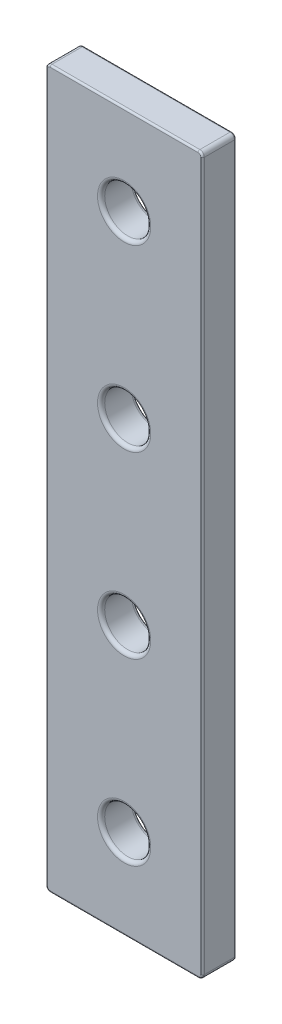
SolidWorks part; units mm, degrees
ref_plane "Front Plane" through (0, 0, 0) normal (0, 0, 1) x (1, 0, 0)
ref_plane "Top Plane" through (0, 0, 0) normal (0, 1, 0) x (1, 0, 0)
ref_plane "Right Plane" through (0, 0, 0) normal (1, 0, 0) x (0, 0, -1)
sketch "Sketch1" plane through (0, 0, 0) normal (0, 0, 1) x (1, 0, 0)
  line L0 (-11.1125, 50.8) -> (-11.1125, -50.8)
  line L1 (-11.1125, 50.8) -> (11.1125, 50.8)
  line L2 (-11.1125, -50.8) -> (11.1125, -50.8)
  line L3 (11.1125, 50.8) -> (11.1125, -50.8)
  line L4 (-11.1125, 0) -> (11.1125, 0) construction
  line L5 (0, 12.7) -> (0, 38.1) construction
  line L6 (-3.175, 38.1) -> (-1.905, 38.1) construction
  circle A0 centre (0, 38.1) radius 3.2639
  circle A2 centre (0, 38.1) radius 3.175 construction
  circle A3 centre (25.4, 38.1) radius 3.2639
  circle A4 centre (25.4, 12.7) radius 3.2639
  circle A5 centre (0, 12.7) radius 3.2639
  circle A6 centre (0, -12.7) radius 3.2639
  circle A7 centre (25.4, -12.7) radius 3.2639
  circle A8 centre (0, -38.1) radius 3.2639
  circle A9 centre (25.4, -38.1) radius 3.2639
  dimension "Thru Hole Diameter" = 6.5278
  dimension "Mounting Fastener Thread Size" = 6.35
  dimension "Width" = 22.225
  dimension "Length" = 101.6
  dimension "Mounting Hole Vert CtoC" = 25.4
  dimension "Mounting Fastener Thread Pitch" = 1.27
  dimension "D1" = 63.5
  dimension "D2" = 11.1125
  dimension "Mounting Hole Horiz CtoC" = 25.4
  dimension "Mounting Hole Vertical Offset" = 12.7
  dimension "Mounting Hole Horizontal Offset" = 11.1125
  dimension "D50" = 2
  dimension "Number of Vertical Holes" = 4
sketch "Sketch2" plane through (0, 0, 0) normal (1, 0, 0) x (0, 0, -1)
  line L0 (-2.3876, 38.1) -> (2.3876, 38.1) construction
  line L1 (2.3876, 38.1) -> (15.0749, 38.1) construction
  dimension "Thickness" = 4.7752
  dimension "Mounting Fastener Thread Length" = 17.4625
sketch "Sketch3" plane through (0, 0, 0) normal (0, 0, 1) x (1, 0, 0)
  line L0 (-11.1125, 50.8) -> (-11.1125, -50.8) construction
  line L1 (-11.1125, -50.8) -> (11.1125, -50.8) construction
  line L2 (11.1125, 50.8) -> (11.1125, -50.8) construction
  line L3 (-11.1125, 50.8) -> (11.1125, 50.8) construction
  line L4 (-11.1125, 50.8) -> (-11.1125, -50.8)
  line L5 (-11.1125, -50.8) -> (11.1125, -50.8)
  line L6 (11.1125, 50.8) -> (11.1125, -50.8)
  line L7 (-11.1125, 50.8) -> (11.1125, 50.8)
extrude "Boss-Extrude1" add sketch "Sketch3" along normal up to vertex (2.3876 mm away) from vertex at -2.3876 starting at point (0, 38.1, -2.3876)
fillet "Fillet1" radius 0.635 4 edges at (11.1125, -50.8, 0) (-11.1125, -50.8, 0) (-11.1125, 50.8, 0) (11.1125, 50.8, 0)
sketch "Sketch4" plane through (0, 0, 2.3876) normal (0, 0, 1) x (1, 0, 0)
  circle A0 centre (0, 38.1) radius 3.2639 construction
  circle A1 centre (0, 38.1) radius 3.2639
extrude "Cut-Extrude1" cut sketch "Sketch4" against normal through all
pattern_linear "LPattern1" count 4 spacing 25.4 along (0, -1, 0) count 2 spacing 25.4 along (-1, 0, 0) of "Cut-Extrude1"
fillet "Fillet2" radius 0.254 16 edges at (10.9265, -50.614, -2.3876) (0, -50.8, -2.3876) (-10.9265, -50.614, -2.3876) (-11.1125, 0, -2.3876) (-10.9265, 50.614, -2.3876) (0, 50.8, -2.3876) (10.9265, 50.614, -2.3876) (10.9265, -50.614, 2.3876) (0, -50.8, 2.3876) (-10.9265, -50.614, 2.3876) (-11.1125, 0, 2.3876) (-10.9265, 50.614, 2.3876) (0, 50.8, 2.3876) (10.9265, 50.614, 2.3876) (11.1125, 0, -2.3876) (11.1125, 0, 2.3876)
fillet "Fillet3" radius 0.508 8 edges at (3.2639, 38.1, -2.3876) (3.2639, 12.7, -2.3876) (3.2639, 38.1, 2.3876) (3.2639, 12.7, 2.3876) (3.2639, -38.1, -2.3876) (3.2639, -12.7, -2.3876) (3.2639, -38.1, 2.3876) (3.2639, -12.7, 2.3876)
equation "\"D1@LPattern1\"=\"Number of Vertical Holes@Sketch1\""
equation "\"D4@LPattern1\"=\"D3@LPattern1\""
equation "\"D3@LPattern1\"=\"Mounting Hole Vert CtoC@Sketch1\""
equation "\"Mounting Hole Horiz CtoC@Sketch1\"=\"Mounting Hole Vert CtoC@Sketch1\""
